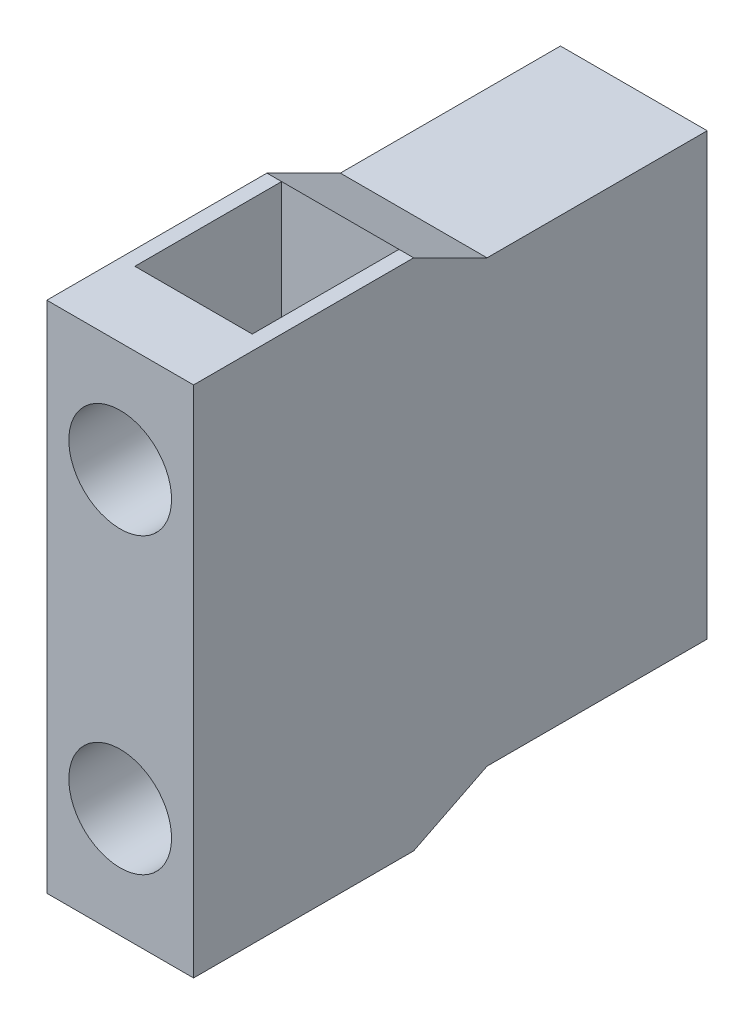
SolidWorks part; units mm, degrees
ref_plane "Front Plane" through (0, 0, 0) normal (0, 0, 1) x (1, 0, 0)
ref_plane "Top Plane" through (0, 0, 0) normal (0, 1, 0) x (1, 0, 0)
ref_plane "Right Plane" through (0, 0, 0) normal (1, 0, 0) x (0, 0, -1)
sketch "Sketch1" plane through (0, 0, 0) normal (1, 0, 0) x (0, 0, -1)
  line L0 (20, 32.5) -> (15, 35)
  line L1 (0, 0) -> (20, 0)
  line L2 (0, 0) -> (0, 35)
  line L3 (0, 35) -> (20, 35)
  line L4 (20, 0) -> (20, 35)
  line L5 (20, 2.5) -> (35, 2.5)
  line L6 (20, 2.5) -> (20, 32.5)
  line L7 (20, 32.5) -> (35, 32.5)
  line L8 (35, 2.5) -> (35, 32.5)
  line L9 (20, 2.5) -> (15, 0)
  dimension "D1" = 35
  dimension "D2" = 30
  dimension "D3" = 2.5
  dimension "D4" = 20
  dimension "D5" = 15
  dimension "D6" = 5
  dimension "D7" = 5
extrude "Boss-Extrude1" add sketch "Sketch1" along normal blind 10 contours L5 L8 L7 L4 | L9 L4 L0 L3 L2 L1
sketch "Sketch2" plane through (0, 0, 0) normal (0, 0, 1) x (1, 0, 0)
  line L0 (10, 35) -> (0, 35) construction
  line L1 (10, 0) -> (10, 35) construction
  circle A0 centre (5, 27.5) radius 3.5
  circle A1 centre (5, 7.5) radius 3.5
  point P4 (5, 35)
  dimension "D1" = 7
  dimension "D2" = 7
  dimension "D3" = 20
  dimension "D4" = 7.5
  dimension "D5" = 5
extrude "Cut-Extrude1" cut sketch "Sketch2" against normal blind 15
sketch "Sketch3" plane through (0, 35, 0) normal (0, 1, 0) x (1, 0, 0)
  line L0 (10, 15) -> (0, 15) construction
  line L1 (9, 5) -> (1, 5)
  line L2 (9, 5) -> (9, 15)
  line L3 (9, 15) -> (1, 15)
  line L4 (1, 5) -> (1, 15)
  line L5 (9, 5) -> (1, 15) construction
  line L6 (9, 15) -> (1, 5) construction
  line L7 (0, 0) -> (0, 15) construction
  point P0 (5, 10)
  dimension "D1" = 10
  dimension "D2" = 8
  dimension "D3" = 1
extrude "Cut-Extrude2" cut sketch "Sketch3" against normal blind 35
sketch "Sketch4" plane through (0, 0, 0) normal (0, 0, 1) x (1, 0, 0)
  line L0 (0, 0) -> (0, 35) construction
  line L1 (0, 15) -> (10, 15)
  line L2 (0, 15) -> (0, 20)
  line L3 (0, 20) -> (10, 20)
  line L4 (10, 15) -> (10, 20)
  line L5 (10, 0) -> (10, 35) construction
  line L6 (10, 35) -> (0, 35) construction
  dimension "D1" = 5
  dimension "D2" = 15
extrude "Boss-Extrude2" add sketch "Sketch4" against normal blind 35
